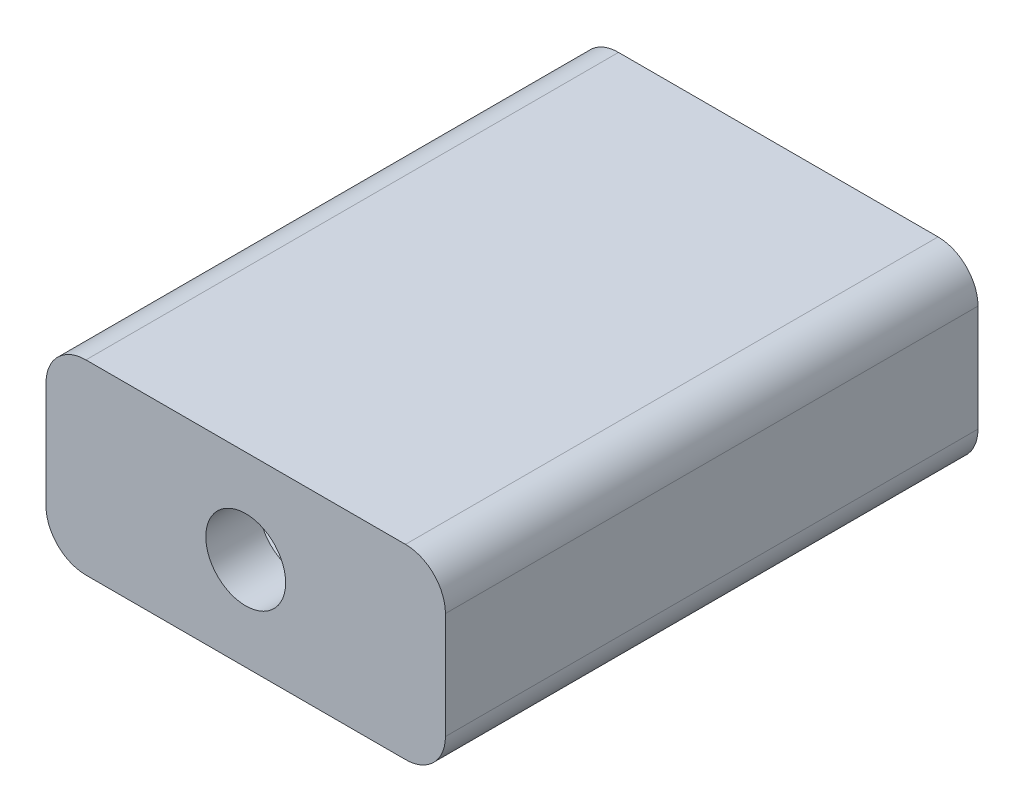
SolidWorks part; units mm, degrees
material "ABS"
ref_plane "Front Plane" through (0, 0, 0) normal (0, 0, 1) x (1, 0, 0)
ref_plane "Top Plane" through (0, 0, 0) normal (0, 1, 0) x (1, 0, 0)
ref_plane "Right Plane" through (0, 0, 0) normal (1, 0, 0) x (0, 0, -1)
sketch "Sketch1" plane through (0, 0, 0) normal (0, 0, 1) x (1, 0, 0)
  line L0 (-12, -7) -> (12, -7)
  line L1 (15, -4) -> (15, 4)
  line L2 (12, 7) -> (-12, 7)
  line L3 (-15, 4) -> (-15, -4)
  arc A0 (12, -7) -> (15, -4) centre (12, -4) ccw
  arc A1 (15, 4) -> (12, 7) centre (12, 4) ccw
  arc A2 (-12, 7) -> (-15, 4) centre (-12, 4) ccw
  arc A3 (-15, -4) -> (-12, -7) centre (-12, -4) ccw
extrude "Boss-Extrude1" add sketch "Sketch1" along normal blind 40
sketch "Sketch2" plane through (0, 0, 0) normal (0, 0, -1) x (-1, 0, 0)
  line L1 (-12.3, -4.5) -> (12.3, -4.5)
  line L2 (-12.3, -4.5) -> (-12.3, 4.5)
  line L3 (-12.3, 4.5) -> (12.3, 4.5)
  line L4 (12.3, -4.5) -> (12.3, 4.5)
  line L5 (-12.3, -4.5) -> (12.3, 4.5) construction
  line L6 (-12.3, 4.5) -> (12.3, -4.5) construction
  point P0 (0, 0)
extrude "Cut-Extrude1" cut sketch "Sketch2" against normal blind 36
sketch "Sketch3" plane through (0, 0, 40) normal (0, 0, 1) x (1, 0, 0)
  circle A0 centre (0, 0) radius 3
extrude "Cut-Extrude2" cut sketch "Sketch3" against normal blind 4.5
